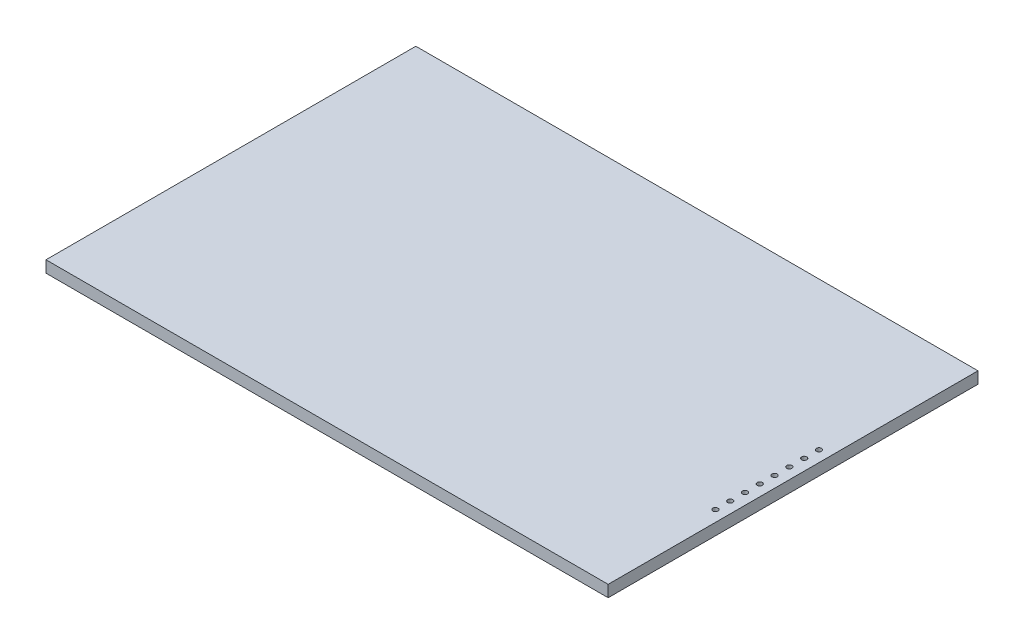
SolidWorks part; units mm, degrees
ref_plane "Front Plane" through (0, 0, 0) normal (0, 0, 1) x (1, 0, 0)
ref_plane "Top Plane" through (0, 0, 0) normal (0, 1, 0) x (1, 0, 0)
ref_plane "Right Plane" through (0, 0, 0) normal (1, 0, 0) x (0, 0, -1)
sketch "Sketch1" plane through (0, 0, 0) normal (0, 1, 0) x (1, 0, 0)
  line L1 (0, 0) -> (-96.52, 0)
  line L2 (0, 0) -> (0, 63.5)
  line L3 (0, 63.5) -> (-96.52, 63.5)
  line L4 (-96.52, 0) -> (-96.52, 63.5)
  dimension "D1" = 63.5
  dimension "D2" = 96.52
extrude "Boss-Extrude1" add sketch "Sketch1" along normal blind 2
sketch "Sketch2" plane through (0, 2, 0) normal (0, 1, 0) x (1, 0, 0)
  line L0 (-96.52, 0) -> (0, 0) construction
  line L1 (-96.52, 63.5) -> (-96.52, 0) construction
  circle A0 centre (-1.905, 38.1) radius 0.4445
  circle A1 centre (-1.905, 35.56) radius 0.4445
  circle A2 centre (-1.905, 33.02) radius 0.4445
  circle A3 centre (-1.905, 30.48) radius 0.4445
  circle A4 centre (-1.905, 27.94) radius 0.4445
  circle A5 centre (-1.905, 25.4) radius 0.4445
  circle A6 centre (-1.905, 22.86) radius 0.4445
  circle A7 centre (-1.905, 20.32) radius 0.4445
  dimension "D3" = 0.889
  dimension "D1" = 38.1
  dimension "D2" = 94.615
  dimension "D4" = 8
extrude "Cut-Extrude1" cut sketch "Sketch2" against normal through all
